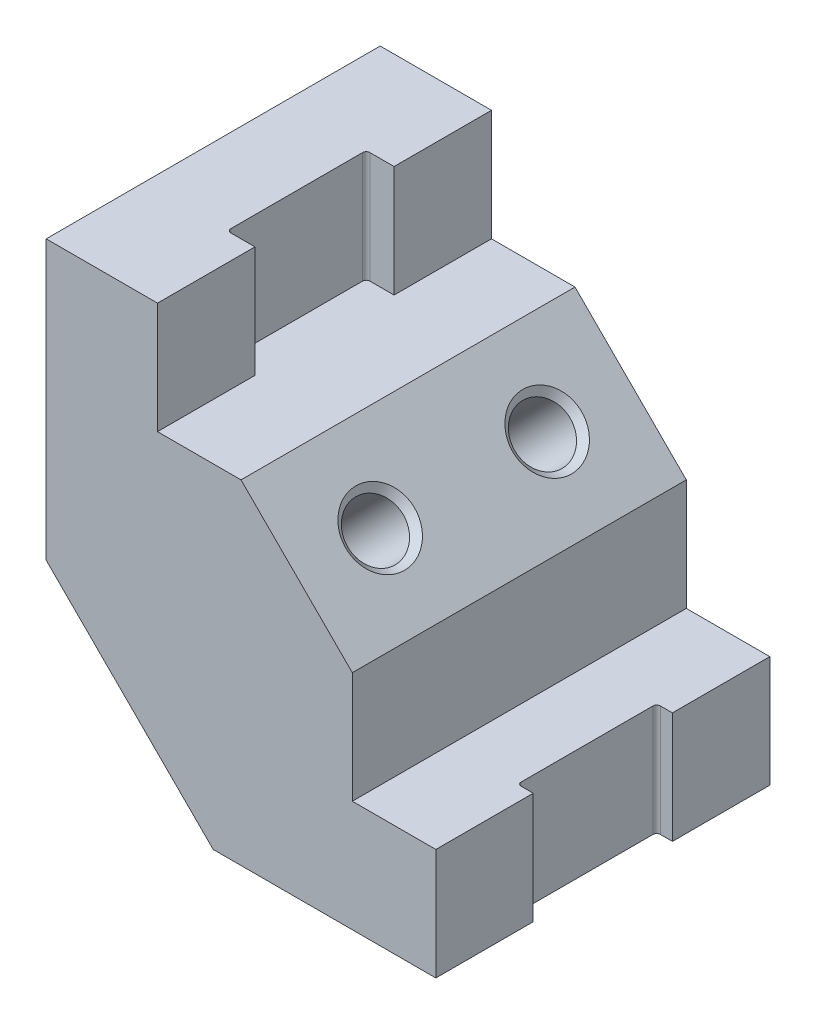
SolidWorks part; units mm, degrees
ref_plane "Front Plane" through (0, 0, 0) normal (0, 0, 1) x (1, 0, 0)
ref_plane "Top Plane" through (0, 0, 0) normal (0, 1, 0) x (1, 0, 0)
ref_plane "Right Plane" through (0, 0, 0) normal (1, 0, 0) x (0, 0, -1)
sketch "Sketch1" plane through (0, 0, 0) normal (0, 0, 1) x (1, 0, 0)
  line L0 (0, 0) -> (0, -63.5)
  line L1 (0, -63.5) -> (38.1, -101.6)
  line L2 (38.1, -101.6) -> (88.9, -101.6)
  line L3 (88.9, -101.6) -> (88.9, -76.2)
  line L4 (88.9, -76.2) -> (69.85, -76.2)
  line L5 (69.85, -76.2) -> (69.85, -50.8)
  line L6 (69.85, -50.8) -> (44.45, -25.4)
  line L7 (44.45, -25.4) -> (25.4, -25.4)
  line L8 (25.4, -25.4) -> (25.4, 0)
  line L9 (25.4, 0) -> (0, 0)
  point P3 (0, 0)
  point P12 (0, 0)
  point P13 (79.375, -76.2)
  point P14 (63.5, -101.6)
  dimension "D1" = 101.6
  dimension "D2" = 88.9
  dimension "D3" = 38.1
  dimension "D4" = 45
  dimension "D5" = 25.4
  dimension "D6" = 44.45
  dimension "D7" = 25.4
  dimension "D8" = 50.8
  dimension "D9" = 76.2
extrude "Boss-Extrude1" add sketch "Sketch1" along normal mid plane 76.2
sketch "Sketch2" plane through (9.525, 9.525, 0) normal (0.7071, 0.7071, 0) x (0, 0, -1)
  line L0 (0, 0) -> (0, -134.7038) construction
  line L1 (-38.1, -134.7038) -> (38.1, -134.7038) construction
  line L2 (-38.1, -85.3124) -> (38.1, -85.3124) construction
  circle A0 centre (-19.05, -67.3546) radius 6.35
  circle A1 centre (19.05, -67.3546) radius 6.35
  point P9 (0, 0)
  point P10 (0, 0)
  dimension "D1" = 12.7
  dimension "D2" = 38.1
  dimension "D3" = 17.9578
extrude "Cut-Extrude1" cut sketch "Sketch2" against normal through all
chamfer "Chamfer1" distance 1.524 angle 45 4 edges at (11.3868, -74.8868, -19.05) (11.3868, -74.8868, 19.05) (52.6618, -33.6118, -19.05) (52.6618, -33.6118, 19.05)
sketch "Sketch3" plane through (0, 0, 0) normal (0, 1, 0) x (1, 0, 0)
  line L0 (25.4, -38.1) -> (25.4, 38.1) construction
  line L1 (25.4, 15.875) -> (19.05, 15.875)
  line L2 (25.4, 15.875) -> (25.4, -15.875)
  line L3 (25.4, -15.875) -> (19.05, -15.875)
  line L4 (19.05, 15.875) -> (19.05, -15.875)
  line L5 (0, 0) -> (88.9, 0) construction
  line L6 (88.9, -38.1) -> (88.9, 38.1) construction
  dimension "D1" = 31.75
  dimension "D2" = 6.35
extrude "Cut-Extrude2" cut sketch "Sketch3" against normal up to surface (25.4 mm away) up to face at (34.925, -25.4, 0)
sketch "Sketch4" plane through (0, -76.2, 0) normal (0, 1, 0) x (1, 0, 0)
  line L0 (88.9, -38.1) -> (88.9, 38.1) construction
  line L1 (88.9, 15.875) -> (85.3097, 15.875)
  line L2 (88.9, 15.875) -> (88.9, -15.875)
  line L3 (88.9, -15.875) -> (85.3097, -15.875)
  line L4 (85.3097, 15.875) -> (85.3097, -15.875)
  line L5 (19.05, -15.875) -> (25.4, -15.875) construction
  line L6 (25.4, 15.875) -> (19.05, 15.875) construction
  line L7 (19.05, 15.875) -> (19.05, -15.875) construction
  point P8 (-32.4406, 14.0229)
extrude "Cut-Extrude3" cut sketch "Sketch4" against normal through all
fillet "Fillet1" radius 0.8382 4 edges at (85.3097, -88.9, 15.875) (85.3097, -88.9, -15.875) (19.05, -12.7, 15.875) (19.05, -12.7, -15.875)
